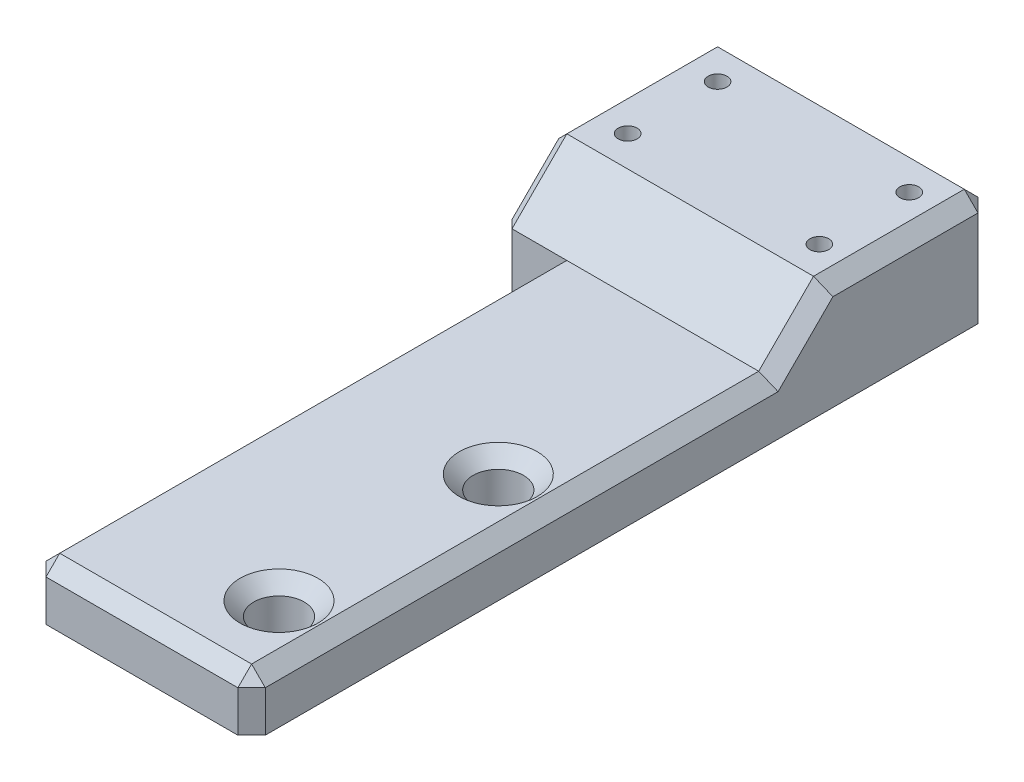
SolidWorks part; units mm, degrees
ref_plane "Front Plane" through (0, 0, 0) normal (0, 0, 1) x (1, 0, 0)
ref_plane "Top Plane" through (0, 0, 0) normal (0, 1, 0) x (1, 0, 0)
ref_plane "Right Plane" through (0, 0, 0) normal (1, 0, 0) x (0, 0, -1)
sketch "Sketch1" plane through (0, 0, 0) normal (0, 1, 0) x (1, 0, 0)
  line L1 (0, 0) -> (31.75, 0)
  line L2 (0, 0) -> (0, 85.725)
  line L3 (0, 85.725) -> (31.75, 85.725)
  line L4 (31.75, 0) -> (31.75, 85.725)
  circle A0 centre (25.4, 9.525) radius 2.921
  circle A1 centre (25.4, 34.925) radius 2.921
  dimension "D3" = 5.842
  dimension "D1" = 31.75
  dimension "D2" = 6.35
  dimension "0.375" = 9.525
  dimension "D4" = 25.4
  dimension "D5" = 50.8
extrude "Boss-Extrude1" add sketch "Sketch1" along normal blind 12.7
sketch "Sketch2" plane through (31.75, 0, 0) normal (1, 0, 0) x (0, 0, -1)
  line L0 (85.725, 12.7) -> (85.725, 0) construction
  line L1 (0, 12.7) -> (60.325, 12.7)
  line L2 (0, 12.7) -> (0, 6.35)
  line L3 (0, 6.35) -> (60.325, 6.35)
  line L4 (60.325, 12.7) -> (60.325, 6.35)
  dimension "D1" = 25.4
  dimension "D2" = 6.35
extrude "Cut-Extrude1" cut sketch "Sketch2" against normal through all
sketch "Sketch3" plane through (0, 0, 0) normal (0, -1, 0) x (1, 0, 0)
  line L0 (0, -85.725) -> (0, 0) construction
  line L2 (31.75, -85.725) -> (0, -85.725) construction
  line L3 (0, 0) -> (6.35, 0)
  line L4 (0, 0) -> (0, -60.325)
  line L5 (0, -60.325) -> (6.35, -60.325)
  line L6 (6.35, 0) -> (6.35, -60.325)
  circle A0 centre (27.2796, -70.231) radius 1.0922
  circle A1 centre (5.08, -80.645) radius 1.0922
  circle A2 centre (27.2796, -80.645) radius 1.0922
  circle A3 centre (5.08, -70.231) radius 1.0922
  dimension "D1" = 2.1844
  dimension "D2" = 22.1996
  dimension "D3" = 5.08
  dimension "D4" = 5.08
  dimension "D5" = 6.35
  dimension "D6" = 10.414
  dimension "2.625" = 60.325
extrude "Cut-Extrude2" cut sketch "Sketch3" against normal through all
chamfer "Chamfer1" distance 6.35 angle 45 1 edges at (15.875, 12.7, -60.325)
chamfer "Chamfer2" distance 1.5875 angle 45 15 edges at (25.4, 6.35, -12.446) (25.4, 6.35, -37.846) (31.75, 6.35, -85.725) (31.75, 3.175, 0) (6.35, 3.175, 0) (6.35, 6.35, -30.1625) (19.05, 6.35, 0) (31.75, 6.35, -30.1625) (31.75, 9.525, -63.5) (31.75, 12.7, -76.2) (0, 6.35, -85.725) (15.875, 12.7, -85.725) (0, 12.7, -76.2) (0, 9.525, -63.5) (0, 3.175, -60.325)
